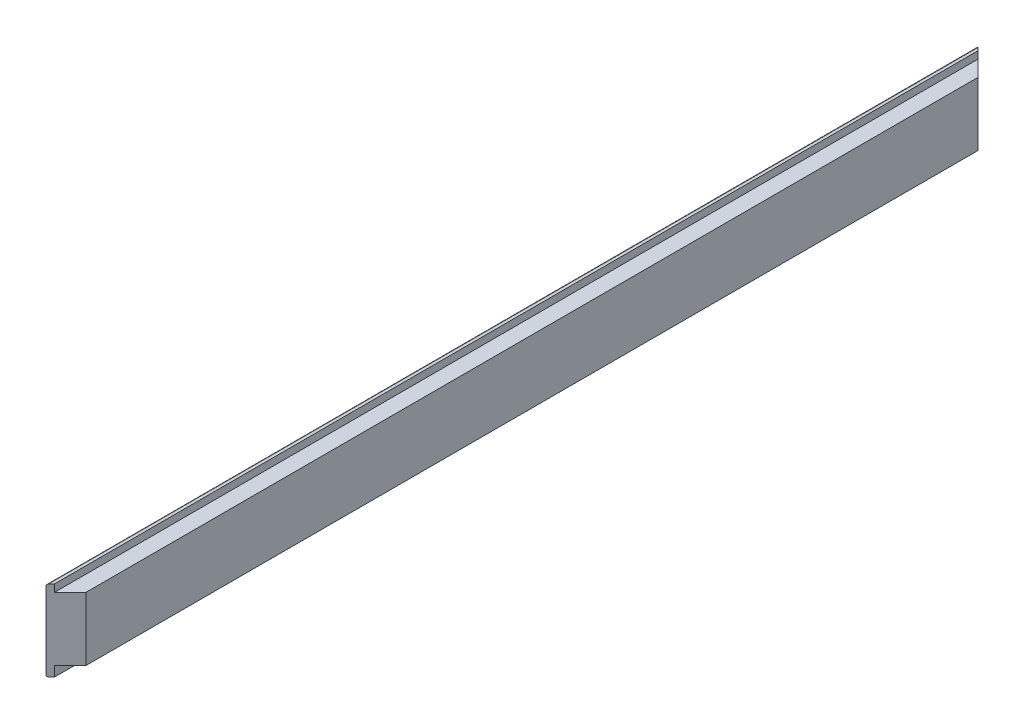
SolidWorks part; units mm, degrees
ref_plane "Front Plane" through (0, 0, 0) normal (0, 0, 1) x (1, 0, 0)
ref_plane "Top Plane" through (0, 0, 0) normal (0, 1, 0) x (1, 0, 0)
ref_plane "Right Plane" through (0, 0, 0) normal (1, 0, 0) x (0, 0, -1)
sketch "Sketch1" plane through (0, 0, 0) normal (0, 0, 1) x (1, 0, 0)
  line L1 (0, 0) -> (19.05, 0)
  line L2 (0, 0) -> (0, 77)
  line L3 (0, 77) -> (19.05, 77)
  line L4 (19.05, 0) -> (19.05, 77)
  line L5 (19.05, 77) -> (4.05, 77)
  line L6 (19.05, 77) -> (19.05, 70)
  line L7 (19.05, 70) -> (4.05, 70)
  line L8 (4.05, 77) -> (4.05, 70)
  line L9 (19.05, 0) -> (4.05, 0)
  line L10 (19.05, 0) -> (19.05, 9.525)
  line L11 (19.05, 9.525) -> (4.05, 9.525)
  line L12 (4.05, 0) -> (4.05, 9.525)
  dimension "D3" = 15
  dimension "D4" = 9.525
  dimension "D5" = 7
  dimension "D1" = 77
  dimension "D2" = 19.05
extrude "Boss-Extrude1" add sketch "Sketch1" along normal mid plane 889.1 contours L1 L12 L11 L4 L7 L8 L3 L2
fillet "Fillet1" radius 1.5875 2 edges at (0, 0, 0) (0, 77, 0)
sketch "Sketch2" plane through (0, 77, 0) normal (0, 1, 0) x (1, 0, 0)
  line L0 (0, -444.55) -> (19.05, -425.5)
  line L1 (19.05, -444.55) -> (19.05, 444.55) construction
  line L2 (19.05, -425.5) -> (19.05, -444.55)
  line L3 (19.05, -444.55) -> (0, -444.55)
  line L4 (0, 444.55) -> (19.05, 425.5)
  line L5 (19.05, 425.5) -> (19.05, 444.55)
  line L6 (19.05, 444.55) -> (0, 444.55)
extrude "Cut-Extrude1" cut sketch "Sketch2" against normal through all both and the other way through all
sketch "Sketch3" plane through (0, 9.525, 0) normal (0, -1, 0) x (1, 0, 0)
  line L0 (11.55, -425.5) -> (11.55, -410.5) construction
  line L1 (19.05, -425.5) -> (4.05, -425.5) construction
  line L3 (10.4775, 0) -> (-10.4775, 0) construction
  line L4 (4.05, 440.5) -> (4.05, -440.5) construction
  point P0 (11.55, -410.5)
  point P13 (11.55, 410.5)
  point P16 (11.55, 0)
  dimension "D1" = 15
hole_wizard "Ø7.9 (7.9) Diameter Hole1" positions "Sketch4" profile "Sketch5" hole size "Ø7.9" standard "ISO"
sketch "Sketch4" plane through (0, 9.525, 0) normal (0, -1, 0) x (-1, 0, 0)
  point P0 (-11.55, -410.5)
  point P3 (-11.55, 410.5)
  point P7 (-11.55, 0)
sketch "Sketch5" plane through (11.55, 9.525, 410.5) normal (1, 0, 0) x (0, 0, -1)
  line L0 (0, 0) -> (0, 17.3734)
  line L1 (0, 17.3734) -> (3.95, 15)
  line L2 (3.95, 15) -> (3.95, 0)
  line L5 (3.95, 0) -> (0, 0)
  line L10 (0, 17.3734) -> (-3.95, 15) construction
  line L11 (0, -6.35) -> (0, 107.95) construction
  dimension "Hole Dia." = 7.9
  dimension "Hole Depth" = 15
  dimension "Drill Angle" = 118
equation "\"SquareSize\" = 5cm"
equation "\"TileCountX\"=12"
equation "\"TileCountY\"= 8"
equation "\"BottomBoardXSize\" = 880mm"
equation "\"BottomBoardYSize\" = 580mm"
equation "\"TopBoardXSize\" = 881mm"
equation "\"TopBoardYSize\"= 581mm"
equation "\"GantryHeight\"= 64mm"
equation "\"EncWallThickness\"= 5mm"
equation "\"EncLip\"= 15mm"
equation "\"TopBoardThickness\"= 3mm"
equation "\"BottomBoardThickness\"= .375in"
equation "\"D3@Sketch1\"=\"EncLip\""
equation "\"D4@Sketch1\"=\"BottomBoardThickness\""
equation "\"D1@Boss-Extrude1\"=881mm+2*4.05000000mm"
equation "\"D1@Sketch1\"=\"GantryHeight\"+\"TopBoardThickness\"+10mm"
